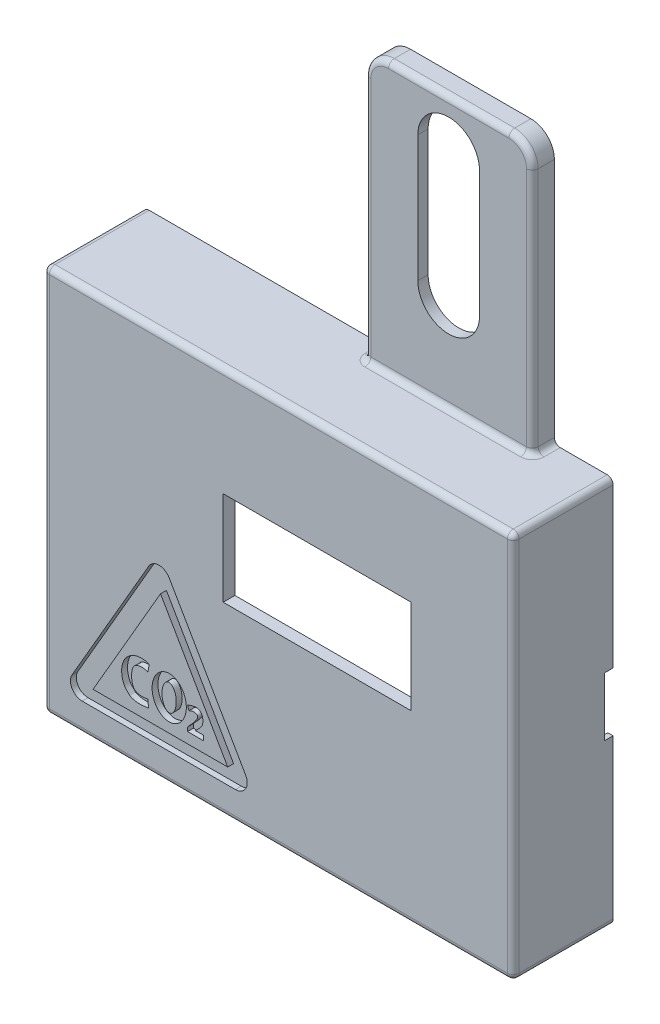
SolidWorks part; units mm, degrees
ref_plane "Front Plane" through (0, 0, 0) normal (0, 0, 1) x (1, 0, 0)
ref_plane "Top Plane" through (0, 0, 0) normal (0, 1, 0) x (1, 0, 0)
ref_plane "Right Plane" through (0, 0, 0) normal (1, 0, 0) x (0, 0, -1)
sketch "Croquis1" plane through (0, 0, 0) normal (0, 0, 1) x (1, 0, 0)
  line L3 (-40, -30.5) -> (40, -30.5)
  line L10 (-40, 35.5) -> (40, 35.5)
  line L12 (-40, 35.5) -> (-40, -30.5)
  line L14 (40, -30.5) -> (40, 35.5)
  point P1 (0, 0)
  dimension "D2" = 40
  dimension "D3" = 66
  dimension "D1" = 80
  dimension "D4" = 35.5
extrude "Saliente-Extruir2" add sketch "Croquis1" along normal blind 17
shell "Vaciado7" thickness 2
sketch "Croquis12" plane through (0, 0, 17) normal (0, 0, 1) x (1, 0, 0)
  line L1 (-9.4, 17) -> (22.6, 17)
  line L2 (-9.4, 17) -> (-9.4, 1)
  line L3 (-9.4, 1) -> (22.6, 1)
  line L4 (22.6, 17) -> (22.6, 1)
  line L5 (-9.4, 17) -> (22.6, 1) construction
  line L6 (-9.4, 1) -> (22.6, 17) construction
  line L9 (40, 35.5) -> (-40, 35.5) construction
  line L11 (40, -30.5) -> (40, 35.5) construction
  point P0 (6.6, 9)
  dimension "D1" = 17.4
  dimension "D2" = 32
  dimension "D3" = 16
  dimension "D4" = 18.5
extrude "Cortar-Extruir9" cut sketch "Croquis12" against normal up to next
sketch "Croquis29" plane through (0, 0, 0) normal (0, 0, -1) x (-1, 0, 0)
  line L9 (-1.5, 77.5) -> (-1.5, 35.5)
  line L10 (-5.5, 81.5) -> (-26, 81.5)
  line L14 (-15.75, 73.25) -> (-15.75, 51.75) construction
  line L15 (-10.5, 73.25) -> (-10.5, 51.75)
  line L16 (-21, 73.25) -> (-21, 51.75)
  line L17 (-30, 35.5) -> (-30, 77.5)
  line L19 (-1.5, 35.5) -> (-30, 35.5)
  line L20 (-40, 35.5) -> (40, 35.5) construction
  line L21 (-40, -30.5) -> (-40, 35.5) construction
  arc A8 (-10.5, 73.25) -> (-21, 73.25) centre (-15.75, 73.25) ccw
  arc A9 (-21, 51.75) -> (-10.5, 51.75) centre (-15.75, 51.75) ccw
  arc A10 (-30, 77.5) -> (-26, 81.5) centre (-26, 77.5) cw
  arc A11 (-1.5, 77.5) -> (-5.5, 81.5) centre (-5.5, 77.5) ccw
  point P2 (-15.75, 62.5)
  dimension "D3" = 10
  dimension "D4" = 4
  dimension "D7" = 5.25
  dimension "D2" = 4
  dimension "D1" = 28.5
  dimension "D5" = 46
  dimension "D6" = 21.5
  dimension "D8" = 14.25
  dimension "D9" = 8.25
extrude "Saliente-Extruir3" add sketch "Croquis29" against normal blind 3.75
sketch "Croquis14" plane through (0, 0, 0) normal (0, 0, -1) x (-1, 0, 0)
  line L8 (39.1, 34.6) -> (-2.4, 34.6)
  line L10 (-29.1, 34.6) -> (-39.1, 34.6)
  line L14 (39.1, 34.6) -> (-2.4, 34.6)
  line L16 (-29.1, 34.6) -> (-39.1, 34.6)
  line L17 (-39.1, -29.6) -> (39.1, -29.6)
  line L21 (-39.1, 34.6) -> (-39.1, -29.6)
  line L22 (-39.1, 34.6) -> (-39.1, -29.6)
  line L23 (39.1, -29.6) -> (39.1, 34.6)
  line L25 (-39.1, -29.6) -> (39.1, -29.6)
  line L28 (39.1, -29.6) -> (39.1, 34.6)
  line L33 (-2.4, 34.6) -> (-2.4, 77.5)
  line L34 (-2.4, 34.6) -> (-2.4, 77.5)
  line L35 (-5.5, 80.6) -> (-26, 80.6)
  line L36 (-5.5, 80.6) -> (-26, 80.6)
  line L37 (-29.1, 77.5) -> (-29.1, 34.6)
  line L38 (-29.1, 77.5) -> (-29.1, 34.6)
  arc A2 (-2.4, 77.5) -> (-5.5, 80.6) centre (-5.5, 77.5) ccw
  arc A9 (-2.4, 77.5) -> (-5.5, 80.6) centre (-5.5, 77.5) ccw
  arc A11 (-26, 80.6) -> (-29.1, 77.5) centre (-26, 77.5) ccw
  arc A12 (-26, 80.6) -> (-29.1, 77.5) centre (-26, 77.5) ccw
  dimension "D1" = 0.9
extrude "Cortar-Extruir11" cut sketch "Croquis14" against normal blind 2
sketch "Croquis16" plane through (-40, 0, 0) normal (-1, 0, 0) x (0, 0, 1)
  line L1 (2, -6.75) -> (12, -6.75)
  line L2 (2, -6.75) -> (2, -18.75)
  line L3 (2, -18.75) -> (12, -18.75)
  line L4 (12, -6.75) -> (12, -18.75)
  line L5 (2, -6.75) -> (12, -18.75) construction
  line L6 (2, -18.75) -> (12, -6.75) construction
  line L9 (17, 35.5) -> (17, -30.5) construction
  line L10 (17, -30.5) -> (0, -30.5) construction
  point P0 (7, -12.75)
  dimension "D1" = 5
  dimension "D2" = 11.75
  dimension "D3" = 12
  dimension "D4" = 10
extrude "Cortar-Extruir26" cut sketch "Croquis16" against normal up to next
sketch "Croquis20" plane through (0, 0, 17) normal (0, 0, 1) x (1, 0, 0)
  line L0 (-454.7792, 225.5349) -> (-56.1125, 225.5349) construction
  line L1 (-21.9873, -14.4639) -> (-22.2206, -15.6887)
  line L2 (-22.2206, -19.7129) -> (-22.1039, -20.996)
  line L3 (-14.1137, -20.2962) -> (-12.7128, -20.2962)
  line L4 (-12.7128, -20.2962) -> (-12.7128, -21.1148)
  line L5 (-12.7128, -21.1148) -> (-15.4552, -21.1127)
  line L6 (-15.2219, -17.9049) -> (-15.4552, -17.2051)
  line L7 (-20.0626, -3.091) -> (-8.6278, -22.9207)
  line L8 (-8.6278, -22.9207) -> (-31.5522, -22.9207)
  line L9 (-31.5522, -22.9207) -> (-20.0626, -3.091)
  line L13 (-18.5908, -0.0036) -> (-5.5675, -22.5878)
  line L14 (-7.3001, -25.5869) -> (-33.4089, -25.5869)
  line L15 (-35.1394, -22.5842) -> (-22.0538, 0)
  arc A0 (-33.4089, -25.5869) -> (-35.1394, -22.5842) centre (-33.4089, -23.5869) cw
  arc A1 (-5.5675, -22.5878) -> (-7.3001, -25.5869) centre (-7.3001, -23.5869) cw
  arc A2 (-18.5908, -0.0036) -> (-22.0538, 0) centre (-20.3233, -1.0027) ccw
  ellipse E0 centre (-18.587, -17.6701) end of major axis (-18.6269, -21.2385) minor radius 2.9144
  ellipse E1 centre (-18.6019, -17.6678) end of major axis (-18.5746, -19.9003) minor radius 1.2154
  spline S0 degree 3 poles (-22.1039, -20.996) (-23.2806, -21.1431) (-24.1884, -21.2543) (-25.2534, -20.7627) (-25.3033, -20.7397) (-25.3311, -20.685) (-25.37, -20.6461) (-25.7538, -20.2623) (-26.0863, -20.026) (-26.3032, -19.538) (-27.1496, -17.6334) (-26.5926, -15.2742) (-24.6118, -14.4639) (-23.7526, -14.1124) (-22.8405, -14.1226) (-21.9873, -14.4639) knots 0 0 0 0 1 1 1 2 2 2 3 3 3 4 4 4 5 5 5 5
  spline S1 degree 3 poles (-22.2206, -15.6887) (-22.4733, -15.6303) (-22.7201, -15.5329) (-22.9788, -15.5137) (-23.2509, -15.4935) (-23.5248, -15.536) (-23.7953, -15.572) (-25.2122, -15.7609) (-25.1226, -18.0593) (-24.7868, -18.9547) (-24.3978, -19.9921) (-23.0425, -19.8499) (-22.2206, -19.7129) knots 0 0 0 0 1 1 1 2 2 2 3 3 3 4 4 4 4
  spline S2 degree 3 poles (-15.4552, -17.2051) (-13.8664, -16.4107) (-12.6326, -16.7984) (-12.889, -18.7214) (-12.9556, -19.2211) (-13.8315, -19.9883) (-14.1137, -20.2962) knots 0 0 0 0 1 1 1 2 2 2 2
  spline S3 degree 3 poles (-15.4552, -21.1127) (-15.4357, -20.8599) (-15.4967, -20.5875) (-15.3968, -20.3545) (-15.2832, -20.0893) (-12.4455, -17.6716) (-14.4637, -17.6716) (-14.8699, -17.6716) (-14.8849, -17.8207) (-15.2219, -17.9049) knots 0 0 0 0 1 1 1 2 2 2 3 3 3 3
  dimension "D1" = 2
extrude "Cortar-Extruir24" cut sketch "Croquis20" against normal blind 1 contours L13 A2 L15 A0 L14 A1 L8 L9 L7 | S1 L1 S0 L2 | E0 E1 | S3 L5 L4 L3 S2 L6
sketch "Croquis27" plane through (40, 0, 0) normal (1, 0, 0) x (0, 0, -1)
  line L0 (-17, -30.5) -> (0, -30.5) construction
  line L1 (-1.5, 7.5) -> (0, 7.5)
  line L2 (-1.5, 7.5) -> (-1.5, -2.5)
  line L3 (-1.5, -2.5) -> (0, -2.5)
  line L4 (0, 7.5) -> (0, -2.5)
  line L7 (-17, -30.5) -> (-17, 35.5) construction
  dimension "D1" = 1.5
  dimension "D2" = 10
  dimension "D3" = 28
  dimension "D4" = 15.5
extrude "Cortar-Extruir25" cut sketch "Croquis27" against normal up to next
fillet "Redondeo3" radius 1 16 edges at (15.75, 35.5, 3.75) (1.5, 56.5, 3.75) (2.6716, 80.3284, 3.75) (30, 56.5, 3.75) (28.8284, 80.3284, 3.75) (15.75, 81.5, 3.75) (40, 2.5, 17) (0, -30.5, 17) (-40, 2.5, 17) (0, 35.5, 17) (40, -30.5, 8.5) (-40, -30.5, 8.5) (-40, 35.5, 8.5) (1.5, 35.5, 1.875) (30, 35.5, 1.875) (40, 35.5, 8.5)
